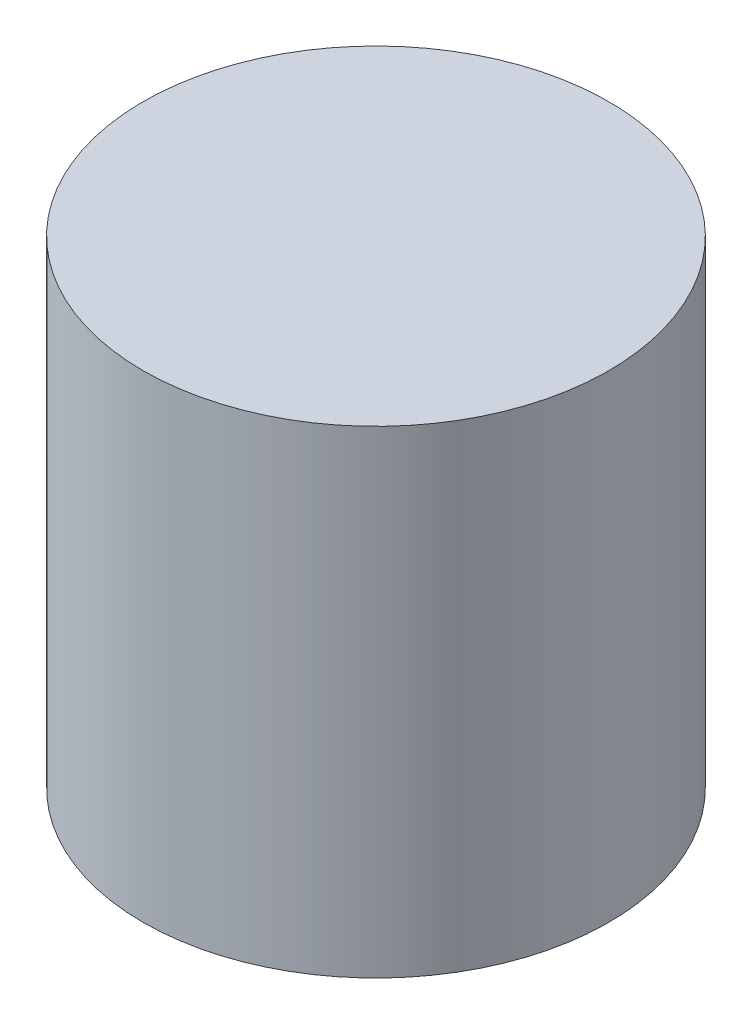
SolidWorks part; units mm, degrees
ref_plane "Front Plane" through (0, 0, 0) normal (0, 0, 1) x (1, 0, 0)
ref_plane "Top Plane" through (0, 0, 0) normal (0, 1, 0) x (1, 0, 0)
ref_plane "Right Plane" through (0, 0, 0) normal (1, 0, 0) x (0, 0, -1)
sketch "Sketch1" plane through (0, 0, 0) normal (0, 1, 0) x (1, 0, 0)
  circle A0 centre (0, 0) radius 97.5
  dimension "D1" = 195
extrude "Boss-Extrude1" add sketch "Sketch1" along normal blind 200
